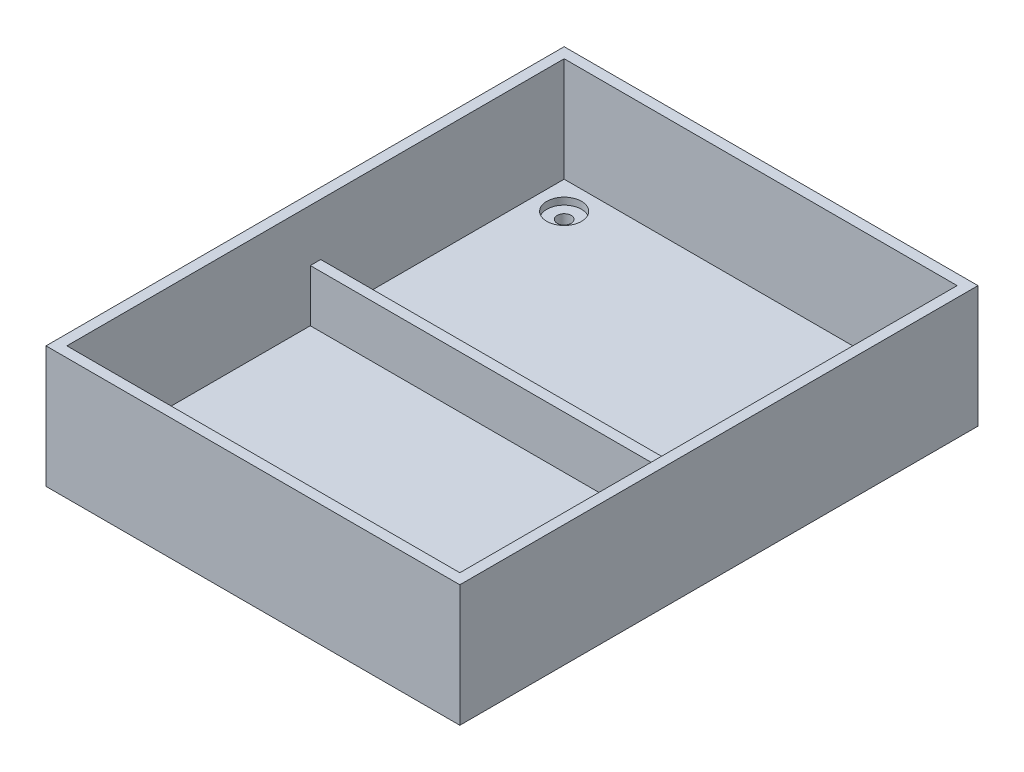
SolidWorks part; units mm, degrees
ref_plane "Front Plane" through (0, 0, 0) normal (0, 0, 1) x (1, 0, 0)
ref_plane "Top Plane" through (0, 0, 0) normal (0, 1, 0) x (1, 0, 0)
ref_plane "Right Plane" through (0, 0, 0) normal (1, 0, 0) x (0, 0, -1)
sketch "Sketch2" plane through (0, 0, 0) normal (0, 1, 0) x (1, 0, 0)
  line L14 (-66.5, 35) -> (-66.5, 38)
  line L15 (-66.5, 38) -> (52.5, 38)
  line L16 (52.5, 38) -> (52.5, -111)
  line L17 (52.5, -111) -> (-66.5, -111)
  line L18 (-66.5, -111) -> (-66.5, 35)
  point P0 (0, 0)
extrude "Boss-Extrude1" add sketch "Sketch2" along normal blind 5
sketch "Sketch3" plane through (0, 5, 0) normal (0, 1, 0) x (1, 0, 0)
  line L1 (-66.5, 38) -> (52.5, 38)
  line L2 (-66.5, 38) -> (-66.5, -111)
  line L3 (-63.5, 35) -> (49.5, 35)
  line L4 (-63.5, 35) -> (-63.5, -35)
  line L5 (-63.5, -35) -> (49.5, -35)
  line L6 (49.5, 35) -> (49.5, -35)
  line L8 (-66.5, -111) -> (52.5, -111)
  line L9 (52.5, 38) -> (52.5, -111)
  line L10 (-63.5, -108) -> (49.5, -108)
  line L11 (-63.5, -108) -> (-63.5, -38)
  line L12 (-63.5, -38) -> (49.5, -38)
  line L13 (49.5, -108) -> (49.5, -38)
extrude "Boss-Extrude3" add sketch "Sketch3" along normal blind 30
sketch "Sketch7" plane through (0, 35, 0) normal (0, 1, 0) x (1, 0, 0)
  line L1 (-63.5, -35) -> (49.5, -35)
  line L2 (-63.5, -35) -> (-63.5, -38)
  line L3 (-63.5, -38) -> (49.5, -38)
  line L4 (49.5, -35) -> (49.5, -38)
extrude "Cut-Extrude2" cut sketch "Sketch7" against normal blind 15
sketch "Sketch8" plane through (0, 5, 0) normal (0, 1, 0) x (1, 0, 0)
  line L0 (-7, 35) -> (-7, -108) construction
  line L3 (49.5, 35) -> (-63.5, 35) construction
  line L4 (-63.5, -108) -> (49.5, -108) construction
  line L5 (-66.5, -36.5) -> (52.5, -36.5) construction
  line L6 (-66.5, 38) -> (-66.5, -111) construction
  line L7 (52.5, -111) -> (52.5, 38) construction
  circle A1 centre (-55.5, 27) radius 5
  circle A2 centre (41.5, 27) radius 5
  circle A3 centre (41.5, -100) radius 5
  circle A4 centre (-55.5, -100) radius 5
extrude "Cut-Extrude3" cut sketch "Sketch8" against normal blind 2
sketch "Sketch9" plane through (0, 3, 0) normal (0, 1, 0) x (1, 0, 0)
  line L0 (-7, 38) -> (-7, -111) construction
  line L1 (52.5, 38) -> (-66.5, 38) construction
  line L2 (-66.5, -111) -> (52.5, -111) construction
  line L3 (-66.5, -36.5) -> (52.5, -36.5) construction
  line L4 (-66.5, 38) -> (-66.5, -111) construction
  line L5 (52.5, -111) -> (52.5, 38) construction
  circle A0 centre (41.5, 27) radius 2
  circle A1 centre (-55.5, 27) radius 2
  circle A2 centre (41.5, -100) radius 2
  circle A3 centre (-55.5, -100) radius 2
extrude "Cut-Extrude4" cut sketch "Sketch9" against normal blind 15
